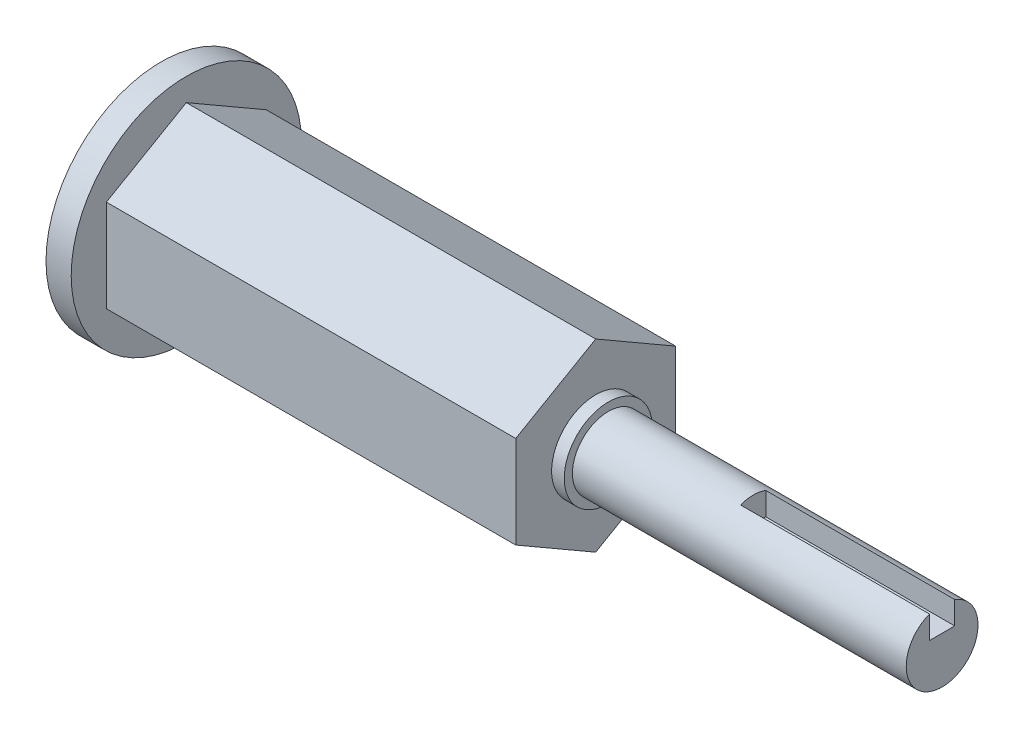
SolidWorks part; units mm, degrees
ref_plane "Front Plane" through (0, 0, 0) normal (1, 0, 0) x (0, 1, 0)
ref_plane "Top Plane" through (0, 0, 0) normal (0, 0, 1) x (0, 1, 0)
ref_plane "Right Plane" through (0, 0, 0) normal (0, 1, 0) x (-1, 0, 0)
sketch "Sketch1" plane through (0, 0, 0) normal (1, 0, 0) x (0, 1, 0)
  circle A0 centre (0, 0) radius 2.85
  dimension "D1" = 5.7
extrude "Boss-Extrude1" add sketch "Sketch1" along normal blind 60
sketch "Sketch2" plane through (0, 0, 0) normal (-1, 0, 0) x (0, -1, 0)
  circle A0 centre (0, 0) radius 9.141
  dimension "D1" = 18.282
extrude "Boss-Extrude2" add sketch "Sketch2" along normal blind 2
sketch "Sketch3" plane through (0, 0, 0) normal (1, 0, 0) x (0, 1, 0)
  line L1 (3.665, 6.348) -> (-3.665, 6.348)
  line L2 (-3.665, 6.348) -> (-7.33, 0)
  line L3 (-7.33, 0) -> (-3.665, -6.348)
  line L4 (-3.665, -6.348) -> (3.665, -6.348)
  line L5 (3.665, -6.348) -> (7.33, 0)
  line L6 (7.33, 0) -> (3.665, 6.348)
  circle A0 centre (0, 0) radius 6.348 construction
  dimension "D2" = 12.6959
  dimension "D1" = 7.33
extrude "Boss-Extrude3" add sketch "Sketch3" along normal blind 32.5
sketch "Sketch4" plane through (60, 0, 0) normal (1, 0, 0) x (0, 1, 0)
  line L0 (0.85, -1) -> (0.85, 1)
  line L1 (0.85, -1) -> (2.85, -1)
  line L3 (0.85, 1) -> (2.85, 1)
  line L4 (2.85, -1) -> (2.85, 1)
  line L5 (0, 0) -> (2.85, 0) construction
  circle A0 centre (0, 0) radius 2.85 construction
  point P4 (2.85, 0)
  dimension "D1" = 2
  dimension "D2" = 2
extrude "Cut-Extrude1" cut sketch "Sketch4" against normal blind 15
sketch "Sketch5" plane through (32.5, 0, 0) normal (1, 0, 0) x (0, 1, 0)
  circle A0 centre (0, 0) radius 3.5
  dimension "D1" = 7
extrude "Boss-Extrude5" add sketch "Sketch5" along normal blind 1
